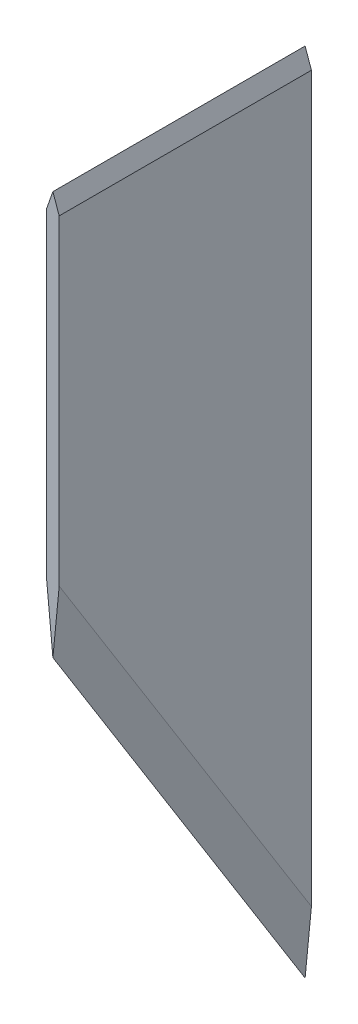
SolidWorks part; units mm, degrees
ref_plane "Front Plane" through (0, 0, 0) normal (1, 0, 0) x (0, 1, 0)
ref_plane "Top Plane" through (0, 0, 0) normal (0, 0, 1) x (0, 1, 0)
ref_plane "Right Plane" through (0, 0, 0) normal (0, 1, 0) x (-1, 0, 0)
sketch "Sketch1" plane through (0, 0, 0) normal (1, 0, 0) x (0, 1, 0)
  line L0 (0, 0) -> (203.2, 0)
  line L1 (203.2, 0) -> (203.2, 63.5)
  line L2 (203.2, 63.5) -> (101.6, 63.5)
  line L3 (101.6, 63.5) -> (0, 0)
  dimension "D1" = 203.2
  dimension "D2" = 101.6
  dimension "D3" = 63.5
  dimension "D4" = 101.6
extrude "Boss-Extrude1" add sketch "Sketch1" along normal blind 3.175
ref_plane "Plane1" through (0, 101.6, 63.5) normal (0, 0.848, 0.53) x (-1, 0, 0)
sketch "Sketch2" plane through (0, 101.6, 63.5) normal (0, 0.848, 0.53) x (-1, 0, 0)
  line L0 (-3.175, -8.6837) -> (-3.175, 1.506)
  line L1 (-3.175, 1.506) -> (0, 1.506)
  line L2 (0, -53.8479) -> (0, 0) construction
  line L3 (0, -8.6837) -> (-1.5875, 0)
  line L4 (-1.5875, 0) -> (-3.175, -8.6837)
  line L5 (-3.175, -53.8479) -> (-3.175, 0) construction
  line L6 (0, 1.506) -> (0, -8.6837)
  line L7 (-3.175, 0) -> (0, 0) construction
  dimension "D1" = 20.72
extrude "Cut-Extrude1" cut sketch "Sketch2" against normal through all both and the other way through all
sketch "Sketch3" plane through (0, 0, 63.5) normal (0, 0, 1) x (1, 0, 0)
  line L0 (0, 198.7071) -> (1.5875, 203.2)
  line L1 (0, 203.2) -> (0, 117.9845) construction
  line L2 (3.175, 203.2) -> (0, 203.2) construction
  line L3 (1.5875, 203.2) -> (3.175, 198.7071)
  line L4 (3.175, 203.2) -> (3.175, 117.9845) construction
  line L5 (3.175, 198.7071) -> (3.175, 209.77)
  line L6 (3.175, 209.77) -> (0, 209.77)
  line L7 (0, 209.77) -> (0, 198.7071)
  dimension "D1" = 38.92
extrude "Cut-Extrude2" cut sketch "Sketch3" against normal through all both and the other way through all
